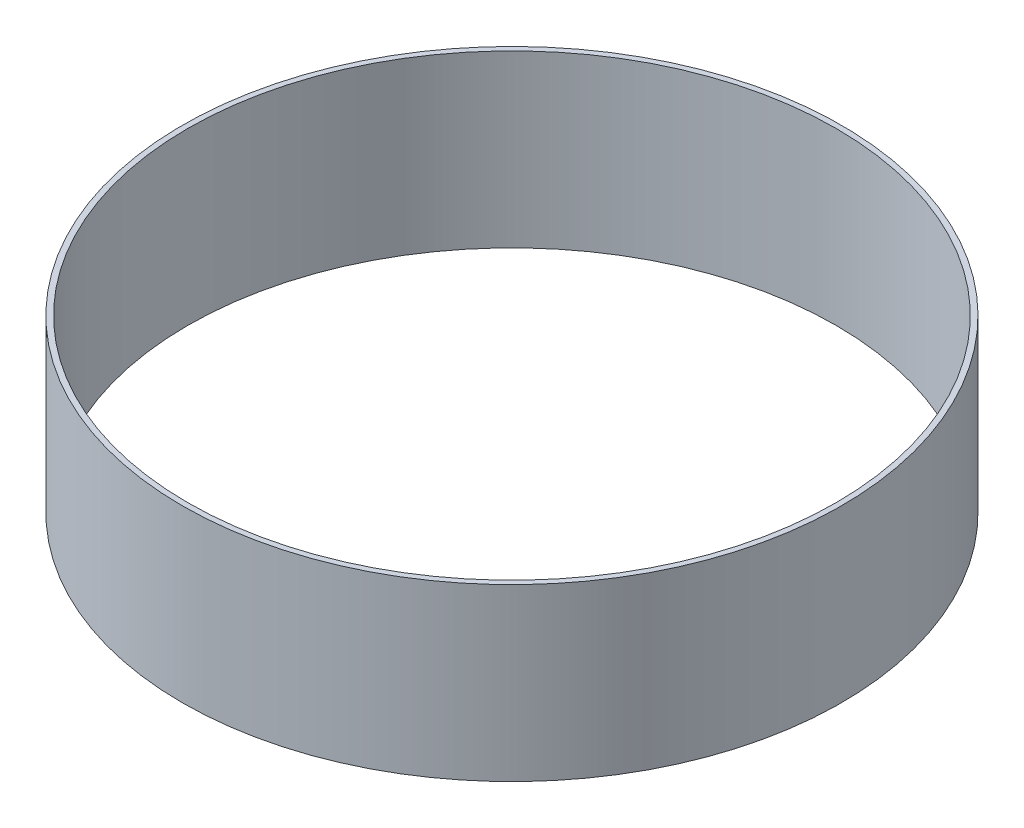
SolidWorks part; units mm, degrees
ref_plane "Front Plane" through (0, 0, 0) normal (0, 0, 1) x (1, 0, 0)
ref_plane "Top Plane" through (0, 0, 0) normal (0, 1, 0) x (1, 0, 0)
ref_plane "Right Plane" through (0, 0, 0) normal (1, 0, 0) x (0, 0, -1)
sketch "Sketch1" plane through (0, 0, 0) normal (0, 1, 0) x (1, 0, 0)
  circle A0 centre (0, 0) radius 20.9
  circle A1 centre (0, 0) radius 21.25
  dimension "D1" = 42.5
  dimension "D2" = 41.8
extrude "Boss-Extrude1" add sketch "Sketch1" along normal blind 11
